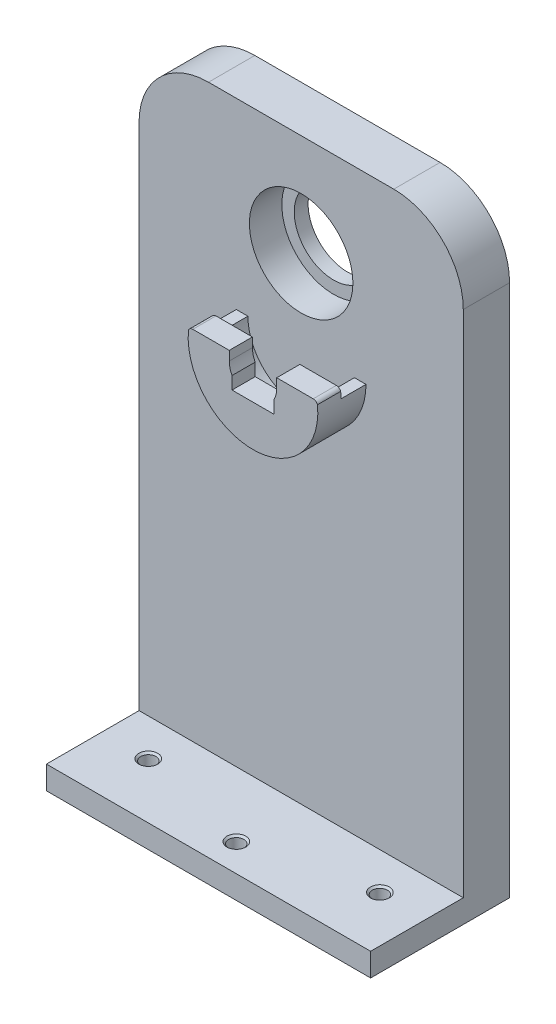
SolidWorks part; units mm, degrees
ref_plane "Front Plane" through (0, 0, 0) normal (0, 0, 1) x (1, 0, 0)
ref_plane "Top Plane" through (0, 0, 0) normal (0, 1, 0) x (1, 0, 0)
ref_plane "Right Plane" through (0, 0, 0) normal (1, 0, 0) x (0, 0, -1)
sketch "Sketch2" plane through (0, 0, 0) normal (0, 0, 1) x (1, 0, 0)
  line L1 (0, 0) -> (-70, 0)
  line L2 (0, 0) -> (0, 115)
  line L3 (-15, 130) -> (-55, 130)
  line L4 (-70, 0) -> (-70, 115)
  arc A0 (0, 115) -> (-15, 130) centre (-15, 115) ccw
  arc A1 (-55, 130) -> (-70, 115) centre (-55, 115) ccw
  circle A2 centre (-35, 108) radius 8.5
  point P7 (0, 130)
  point P10 (-70, 130)
  point P14 (-35, 130)
  dimension "D3" = 15
  dimension "D4" = 17
  dimension "D1" = 130
  dimension "D2" = 70
  dimension "D5" = 22
extrude "Boss-Extrude1" add sketch "Sketch2" along normal blind 10
sketch "Sketch3" plane through (0, 0, 10) normal (0, 0, 1) x (1, 0, 0)
  line L0 (0, 0) -> (0, 115) construction
  line L1 (-70, 0) -> (0, 0)
  line L2 (-70, 0) -> (-70, 5)
  line L3 (-70, 5) -> (0, 5)
  line L4 (0, 0) -> (0, 5)
  circle A0 centre (-35, 108) radius 11.175
  dimension "D2" = 22.35
  dimension "D1" = 5
extrude "Cut-Extrude1" cut sketch "Sketch3" against normal blind 7 contours A0
sketch "Sketch4" plane through (0, 0, 10) normal (0, 0, 1) x (1, 0, 0)
  line L0 (0, 0) -> (0, 115) construction
  line L1 (-70, 0) -> (0, 0)
  line L2 (-70, 0) -> (-70, 5)
  line L3 (-70, 5) -> (0, 5)
  line L4 (0, 0) -> (0, 5)
  dimension "D1" = 5
extrude "Boss-Extrude3" add sketch "Sketch4" along normal blind 20
sketch "Sketch5" plane through (0, 5, 0) normal (0, 1, 0) x (1, 0, 0)
  line L0 (0, -10) -> (-70, -10) construction
  line L1 (0, -30) -> (-70, -30) construction
  line L2 (-70, -30) -> (-70, -10) construction
  line L3 (0, -30) -> (0, -10) construction
  circle A0 centre (-60, -18) radius 1.64
  circle A1 centre (-35, -24) radius 1.64
  circle A2 centre (-10, -18) radius 1.64
  point P12 (-35, -30)
  dimension "D1" = 3.28
  dimension "D2" = 8
  dimension "D3" = 6
  dimension "D4" = 10
  dimension "D5" = 10
extrude "Cut-Extrude2" cut sketch "Sketch5" against normal blind 20
chamfer "Chamfer1" distance 0.4 angle 45 1 edges at (-35, 5, 25.64)
chamfer "Chamfer3" distance 0.4 angle 45 2 edges at (-10, 5, 19.64) (-60, 5, 19.64)
sketch "Sketch6" plane through (0, 0, 10) normal (0, 0, 1) x (1, 0, 0)
  line L0 (-15, 130) -> (-55, 130) construction
  line L1 (-49, 90.5) -> (-21, 90.5)
  circle A0 centre (-35, 90.5) radius 11.5
  circle A1 centre (-35, 90.5) radius 14
  point P5 (-35, 130)
  dimension "D2" = 23
  dimension "D3" = 28
  dimension "D1" = 39.5
extrude "Boss-Extrude4" add sketch "Sketch6" along normal blind 5.4 contours L1 A1 A0
sketch "Sketch7" plane through (0, 0, 15.4) normal (0, 0, 1) x (1, 0, 0)
  line L0 (-49, 90.5) -> (-21, 90.5)
  line L1 (-39.525, 90.5) -> (-30.475, 90.5)
  line L2 (-39.525, 90.5) -> (-39.525, 85.375)
  line L3 (-39.525, 85.375) -> (-30.475, 85.375)
  line L4 (-30.475, 90.5) -> (-30.475, 85.375)
  line L6 (-49, 90.5) -> (-40.125, 90.5)
  line L7 (-49, 90.5) -> (-49, 91.5)
  line L8 (-48, 92.5) -> (-40.125, 92.5)
  line L9 (-40.125, 90.5) -> (-40.125, 92.5)
  line L10 (-21, 90.5) -> (-29.875, 90.5)
  line L11 (-21, 90.5) -> (-21, 91.5)
  line L12 (-22, 92.5) -> (-29.875, 92.5)
  line L13 (-29.875, 90.5) -> (-29.875, 92.5)
  circle A0 centre (-35, 90.5) radius 5.125
  circle A1 centre (-35, 90.5) radius 14
  arc A2 (-21, 91.5) -> (-22, 92.5) centre (-22, 91.5) ccw
  arc A3 (-49, 91.5) -> (-48, 92.5) centre (-48, 91.5) cw
  point P22 (-49, 92.5)
  line M7 (-46.5, 90.5) -> (-49, 90.5)
  arc M8 (-49, 90.5) -> (-21, 90.5) centre (-35, 90.5) ccw
  line M9 (-21, 90.5) -> (-23.5, 90.5)
  arc M10 (-23.5, 90.5) -> (-46.5, 90.5) centre (-35, 90.5) cw
  dimension "D1" = 10.25
  dimension "D4" = 1
  dimension "D2" = 9.05
  dimension "D3" = 2
extrude "Boss-Extrude5" add sketch "Sketch7" along normal blind 5 contours M10 M7 M8 M9 | A0 L0 L4 L3 L2 M10 | A3 A1 L0 L9 L8 M7 | A1 A2 L12 L13 L0 M9
